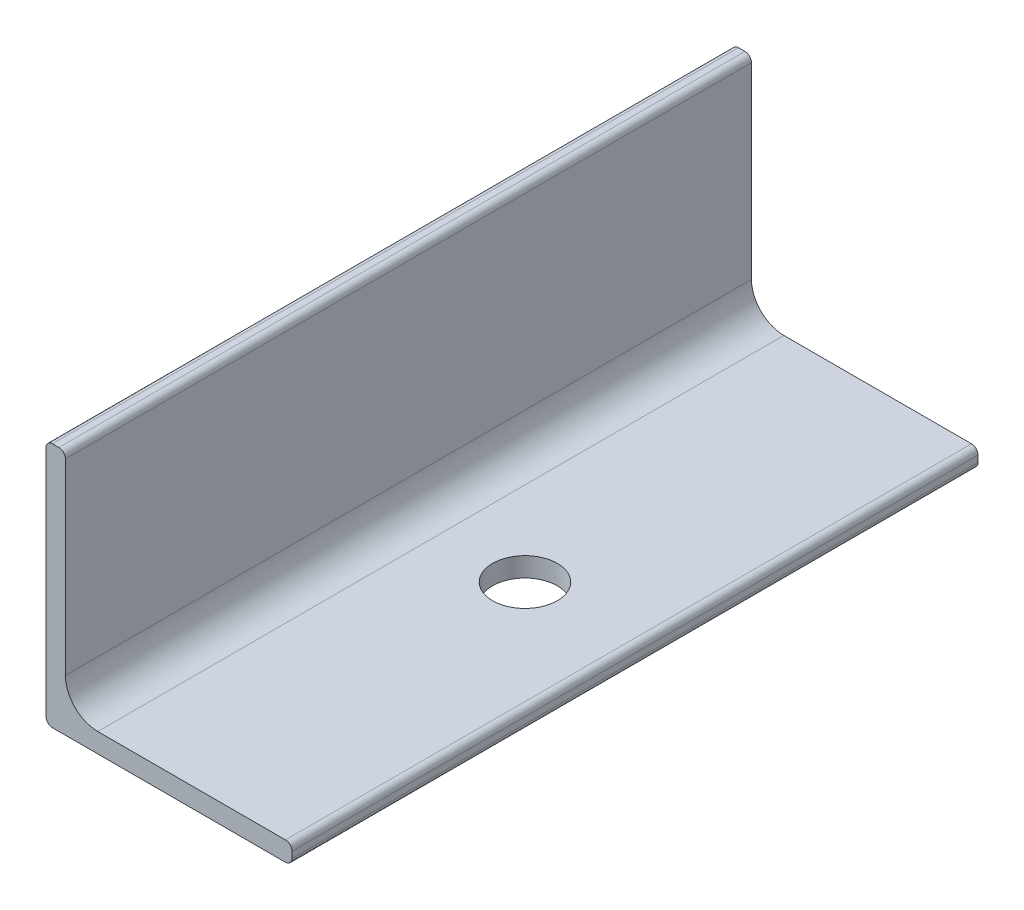
SolidWorks part; units mm, degrees
material "Q235锻制"
ref_plane "前视基准面" through (0, 0, 0) normal (0, 0, 1) x (1, 0, 0)
ref_plane "上视基准面" through (0, 0, 0) normal (0, 1, 0) x (1, 0, 0)
ref_plane "右视基准面" through (0, 0, 0) normal (1, 0, 0) x (0, 0, -1)
sketch "草图1" plane through (0, 0, 0) normal (0, 0, 1) x (1, 0, 0)
  line L0 (0, 1) -> (0, 37)
  line L1 (0, -55) -> (0, 55) construction
  line L2 (1, 38) -> (2, 38)
  line L3 (3, 37) -> (3, 8)
  line L4 (8, 3) -> (37, 3)
  line L5 (38, 2) -> (38, 1)
  line L6 (55, 0) -> (-55, 0) construction
  line L7 (37, 0) -> (1, 0)
  arc A0 (3, 8) -> (8, 3) centre (8, 8) ccw
  arc A1 (38, 1) -> (37, 0) centre (37, 1) cw
  arc A2 (37, 3) -> (38, 2) centre (37, 2) cw
  arc A3 (2, 38) -> (3, 37) centre (2, 37) cw
  arc A4 (0, 37) -> (1, 38) centre (1, 37) cw
  arc A5 (0, 1) -> (1, 0) centre (1, 1) ccw
  point P15 (38, 0)
  point P18 (38, 3)
  point P21 (3, 38)
  point P24 (0, 38)
  point P27 (0, 0)
  dimension "D5" = 5
  dimension "D6" = 1
  dimension "D1" = 38
  dimension "D2" = 38
  dimension "D3" = 3
  dimension "D4" = 3
extrude "凸台-拉伸1" add sketch "草图1" along normal mid plane 106
sketch "草图2" plane through (0, 3, 0) normal (0, 1, 0) x (1, 0, 0)
  line L0 (-20.9, 0) -> (20.9, 0) construction
  line L1 (38, -53) -> (38, 53) construction
  circle A0 centre (21, 0) radius 5
  dimension "D1" = 10
  dimension "D2" = 17
extrude "切除-拉伸1" cut sketch "草图2" against normal through all
